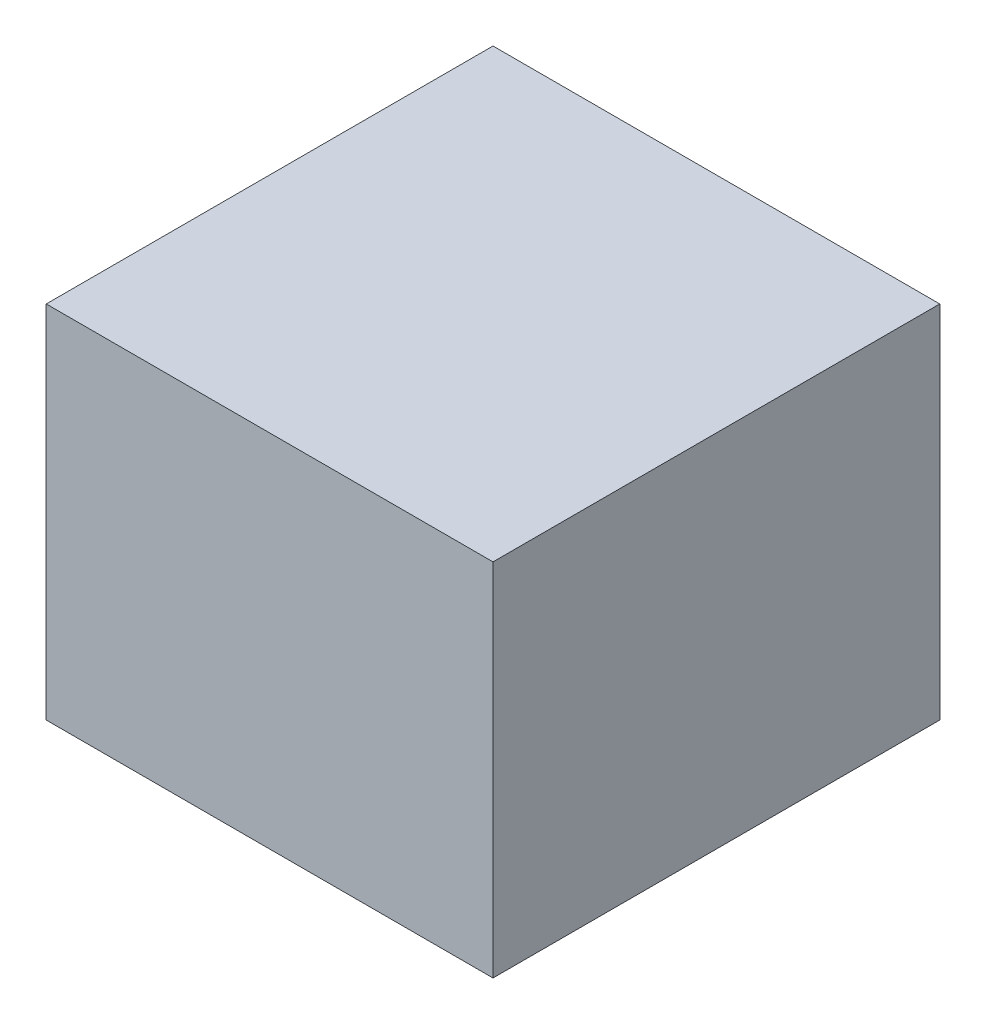
SolidWorks part; units mm, degrees
ref_plane "Front Plane" through (0, 0, 0) normal (0, 0, 1) x (1, 0, 0)
ref_plane "Top Plane" through (0, 0, 0) normal (0, 1, 0) x (1, 0, 0)
ref_plane "Right Plane" through (0, 0, 0) normal (1, 0, 0) x (0, 0, -1)
sketch "Sketch1" plane through (0, 0, 0) normal (0, 1, 0) x (1, 0, 0)
  line L1 (0, 0) -> (45, 0)
  line L2 (0, 0) -> (0, 45)
  line L3 (0, 45) -> (45, 45)
  line L4 (45, 0) -> (45, 45)
  dimension "D1" = 45
extrude "Boss-Extrude1" add sketch "Sketch1" along normal blind 36.3
